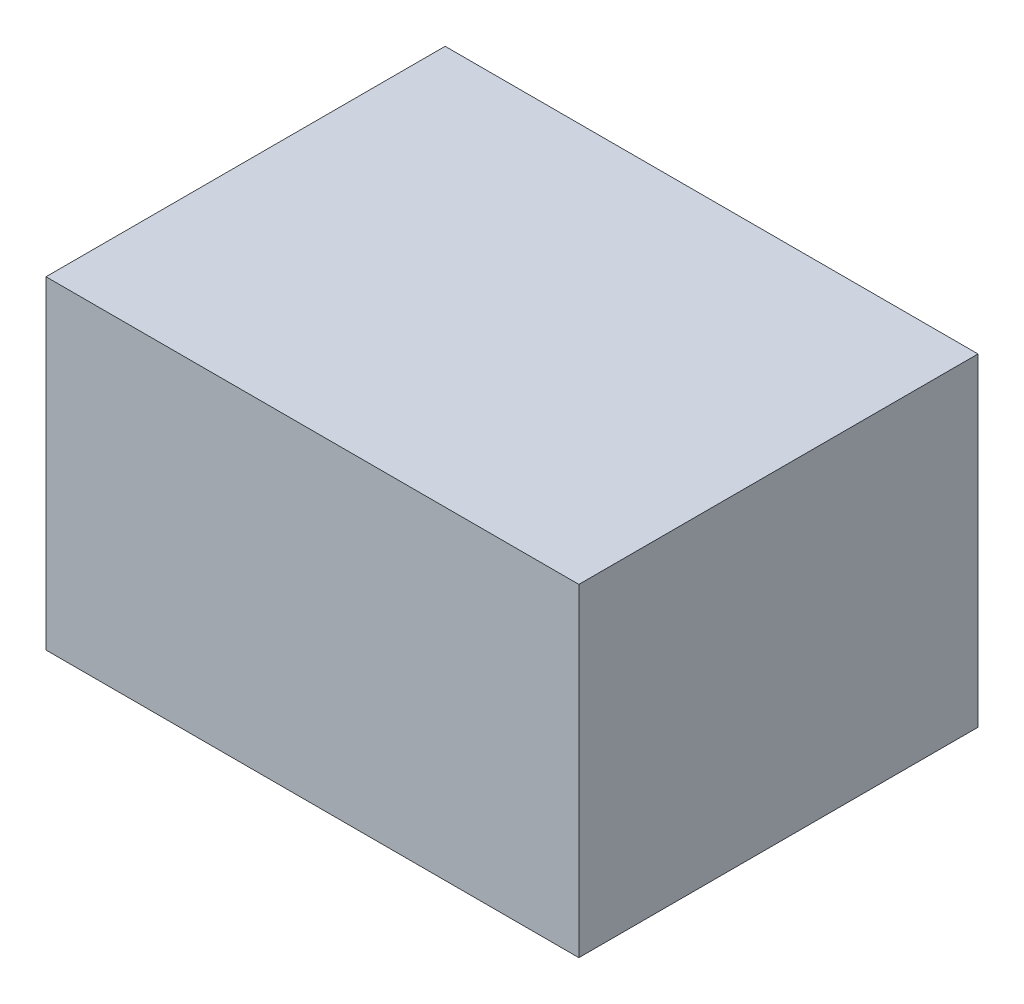
SolidWorks part; units mm, degrees
ref_plane "Front Plane" through (0, 0, 0) normal (0, 0, 1) x (1, 0, 0)
ref_plane "Top Plane" through (0, 0, 0) normal (0, 1, 0) x (1, 0, 0)
ref_plane "Right Plane" through (0, 0, 0) normal (1, 0, 0) x (0, 0, -1)
sketch "Sketch1" plane through (0, 0, 0) normal (0, 0, 1) x (1, 0, 0)
  line L1 (11.35, -6.1) -> (-11.35, -6.1)
  line L2 (11.35, -6.1) -> (11.35, 6.1)
  line L3 (11.35, 6.1) -> (-11.35, 6.1)
  line L4 (-11.35, -6.1) -> (-11.35, 6.1)
  line L5 (11.35, -6.1) -> (-11.35, 6.1) construction
  line L6 (11.35, 6.1) -> (-11.35, -6.1) construction
  point P0 (0, 0)
  dimension "D1" = 22.7
  dimension "D2" = 12.2
extrude "Boss-Extrude1" add sketch "Sketch1" along normal blind 3.5
sketch "Sketch2" plane through (0, 0, 3.5) normal (0, 0, 1) x (1, 0, 0)
  line L1 (11.35, -6.1) -> (-11.35, -6.1)
  line L2 (11.35, -6.1) -> (11.35, 6.1)
  line L3 (11.35, 6.1) -> (-11.35, 6.1)
  line L4 (-11.35, -6.1) -> (-11.35, 6.1)
  line L5 (11.35, -6.1) -> (-11.35, 6.1) construction
  line L6 (11.35, 6.1) -> (-11.35, -6.1) construction
  line L7 (13.35, -8.1) -> (-13.35, -8.1)
  line L8 (13.35, -8.1) -> (13.35, 8.1)
  line L9 (13.35, 8.1) -> (-13.35, 8.1)
  line L10 (-13.35, -8.1) -> (-13.35, 8.1)
  line L11 (13.35, -8.1) -> (-13.35, 8.1) construction
  line L12 (13.35, 8.1) -> (-13.35, -8.1) construction
  point P0 (0, 0)
  point P7 (0, 0)
  dimension "D1" = 2
  dimension "D2" = 2
extrude "Boss-Extrude2" add sketch "Sketch2" against normal blind 20
sketch "Sketch3" plane through (-13.35, 0, 0) normal (-1, 0, 0) x (0, 0, 1)
  line L0 (3.5, 8.1) -> (3.5, -8.1) construction
  line L1 (-3, -5.1) -> (0, -5.1)
  line L2 (-3, -5.1) -> (-3, 5.1)
  line L3 (-3, 5.1) -> (0, 5.1)
  line L4 (0, -5.1) -> (0, 5.1)
  line L5 (-3, -5.1) -> (0, 5.1) construction
  line L6 (-3, 5.1) -> (0, -5.1) construction
  line L8 (-16.5, 8.1) -> (3.5, 8.1) construction
  line L9 (-16.5, -8.1) -> (3.5, -8.1) construction
  point P0 (-1.5, 0)
  dimension "D1" = 3.5
  dimension "D2" = 6.5
  dimension "D3" = 3
  dimension "D4" = 3
extrude "Cut-Extrude1" cut sketch "Sketch3" against normal up to surface (2 mm away) up to face at (-11.35, 0, -8.25)
